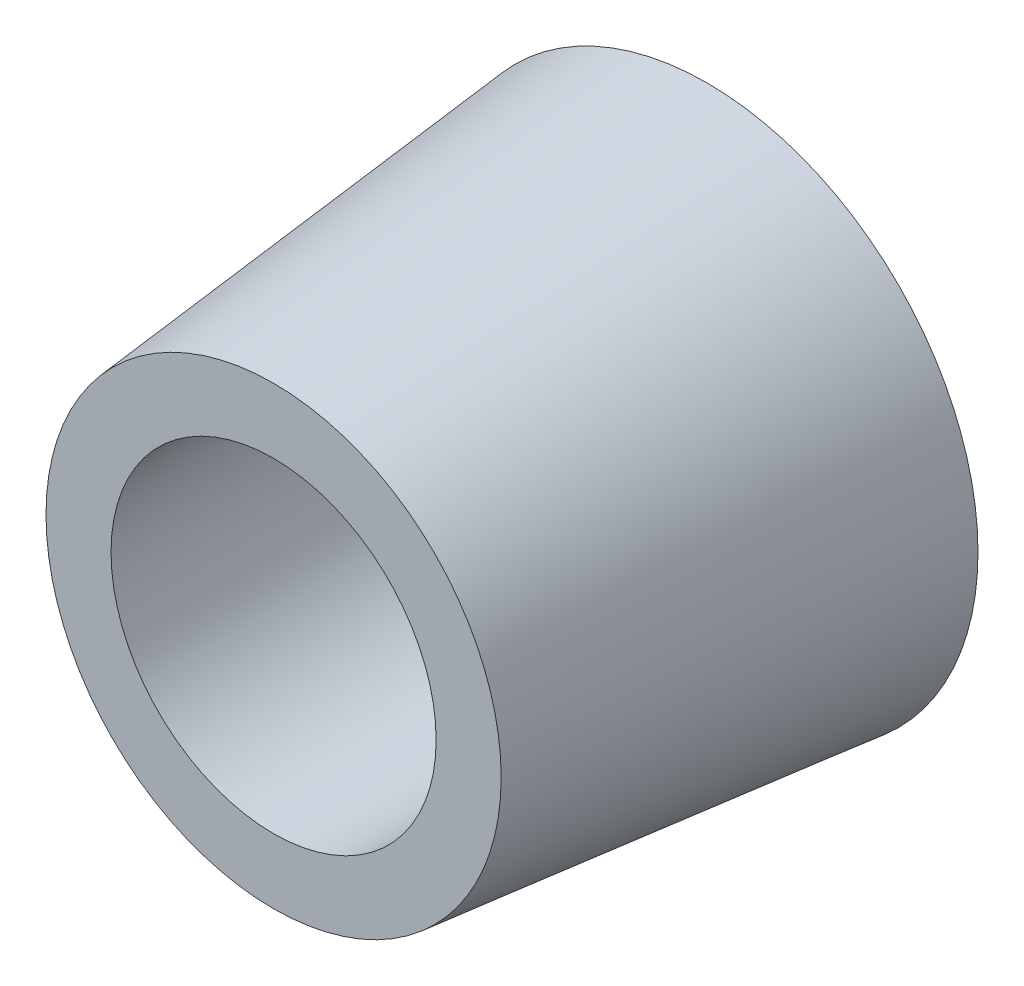
SolidWorks part; units mm, degrees
material "Mosiądz"
ref_plane "Płaszczyzna przednia" through (0, 0, 0) normal (0, 0, 1) x (1, 0, 0)
ref_plane "Płaszczyzna górna" through (0, 0, 0) normal (0, 1, 0) x (1, 0, 0)
ref_plane "Płaszczyzna prawa" through (0, 0, 0) normal (1, 0, 0) x (0, 0, -1)
sketch "Szkic1" plane through (0, 0, 0) normal (0, 0, 1) x (1, 0, 0)
  circle A0 centre (0, 0) radius 2.5
  circle A1 centre (0, 0) radius 1.5
  dimension "D1" = 5
  dimension "D2" = 3
ref_plane "Płaszczyzna1" through (0, 0, 4) normal (0, 0, 1) x (1, 0, 0)
sketch "Szkic2" plane through (0, 0, 4) normal (0, 0, 1) x (1, 0, 0)
  circle A0 centre (0, 0) radius 2.1
  circle A1 centre (0, 0) radius 1.5
  dimension "D1" = 4.2
  dimension "D2" = 3
loft "Wyciągnięcie po profilach1" add section "Szkic1" section "Szkic2"
sketch "Szkic3" plane through (0, 0, 4) normal (0, 0, 1) x (1, 0, 0)
  circle A0 centre (0, 0) radius 1.5
  dimension "D1" = 3
extrude "Wytnij-wyciągnięcie1" cut sketch "Szkic3" against normal blind 10
